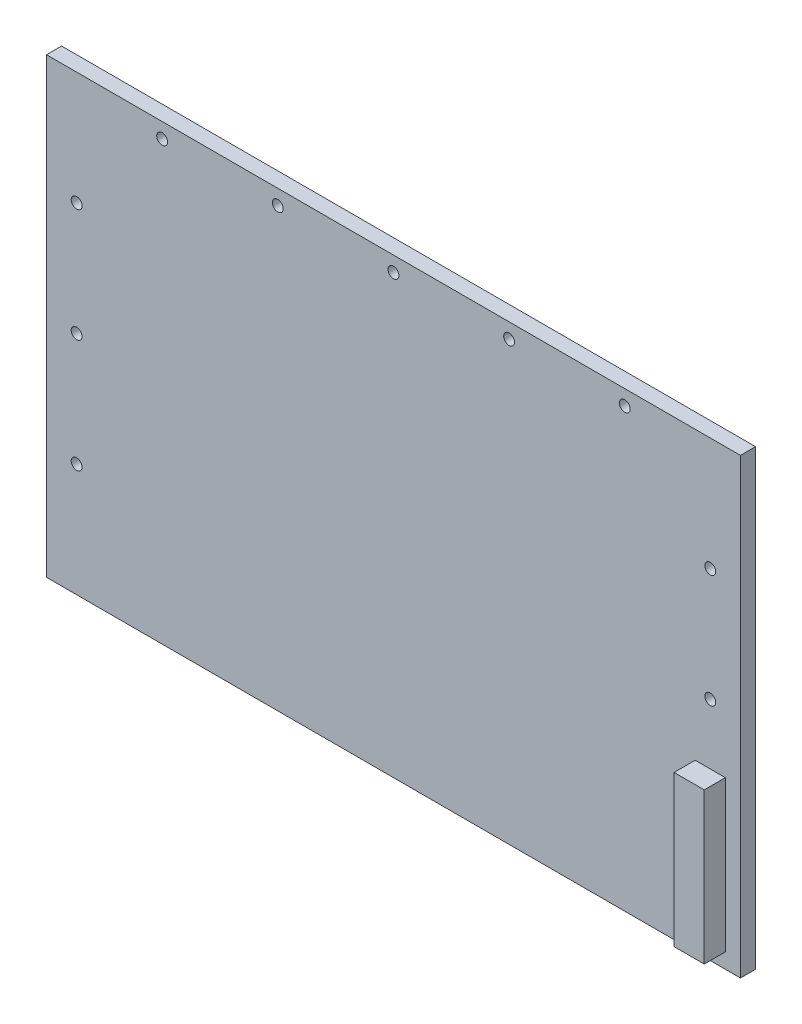
SolidWorks part; units mm, degrees
ref_plane "Płaszczyzna przednia" through (0, 0, 0) normal (0, 0, 1) x (1, 0, 0)
ref_plane "Płaszczyzna górna" through (0, 0, 0) normal (0, 1, 0) x (1, 0, 0)
ref_plane "Płaszczyzna prawa" through (0, 0, 0) normal (1, 0, 0) x (0, 0, -1)
sketch "Szkic1" plane through (0, 0, 0) normal (0, 0, 1) x (1, 0, 0)
  line L1 (-115, -75) -> (115, -75)
  line L2 (-115, -75) -> (-115, 75)
  line L3 (-115, 75) -> (115, 75)
  line L4 (115, -75) -> (115, 75)
  line L5 (0, 75) -> (0, -75) construction
  line L6 (-115, 0) -> (115, 0) construction
  point P0 (0, 0)
  dimension "D1" = 230
  dimension "D2" = 150
extrude "Dodanie-wyciągnięcie1" add sketch "Szkic1" along normal blind 5
sketch "Szkic3" plane through (0, 0, 0) normal (0, 0, -1) x (-1, 0, 0)
  line L0 (0, 75) -> (0, -75) construction
  line L1 (-115, 75) -> (115, 75) construction
  line L2 (115, -75) -> (-115, -75) construction
  point P0 (105, 37.5)
  point P1 (105, 0)
  point P3 (105, -37.5)
  point P16 (-105, 0)
  point P17 (-105, 37.5)
hole_wizard "Pogłębienie walcowe pod M3 Śrubę z łbem stożkowym ściętym1" positions "Szkic3" profile "Szkic4" counterbore size "M3" standard "DIN"
sketch "Szkic4" plane through (-105, 37.5, 0) normal (1, 0, 0) x (0, 1, 0)
  line L0 (0, 0) -> (0, 7.7815)
  line L1 (0, 7.7815) -> (1.8, 6.7)
  line L2 (1.8, 6.7) -> (1.8, 2.4)
  line L3 (1.8, 2.4) -> (3.5, 2.4)
  line L4 (3.5, 2.4) -> (3.5, 0)
  line L5 (3.5, 0) -> (0, 0)
  line L10 (0, 7.7815) -> (-1.8, 6.7) construction
  line L11 (0, -6.35) -> (0, 107.95) construction
  dimension "Średnica otworu" = 3.6
  dimension "Głębokość otworu" = 6.7
  dimension "Średnica pogłębienia walcowego" = 7
  dimension "Głębokość pogłębienia walcowego" = 2.4
  dimension "Kąt wiertła" = 118
sketch "Szkic5" plane through (0, 0, 0) normal (0, 0, -1) x (-1, 0, 0)
  line L0 (-115, 75) -> (115, 75) construction
  line L1 (-115, -75) -> (-115, 75) construction
  point P0 (-76.6667, 70)
  point P5 (-38.3333, 70)
  point P7 (0, 70)
  point P8 (38.3333, 70)
  point P9 (76.6667, 70)
  dimension "D1" = 5
  dimension "D2" = 38.3333
  dimension "D3" = 5
hole_wizard "Pogłębienie walcowe pod M3 Śrubę z łbem stożkowym ściętym2" positions "Szkic5" profile "Szkic6" counterbore size "M3" standard "DIN"
sketch "Szkic6" plane through (76.6667, 70, 0) normal (1, 0, 0) x (0, 1, 0)
  line L0 (0, 0) -> (0, 7.7815)
  line L1 (0, 7.7815) -> (1.8, 6.7)
  line L2 (1.8, 6.7) -> (1.8, 2.4)
  line L3 (1.8, 2.4) -> (3.5, 2.4)
  line L4 (3.5, 2.4) -> (3.5, 0)
  line L5 (3.5, 0) -> (0, 0)
  line L10 (0, 7.7815) -> (-1.8, 6.7) construction
  line L11 (0, -6.35) -> (0, 107.95) construction
  dimension "Średnica otworu" = 3.6
  dimension "Głębokość otworu" = 6.7
  dimension "Średnica pogłębienia walcowego" = 7
  dimension "Głębokość pogłębienia walcowego" = 2.4
  dimension "Kąt wiertła" = 118
sketch "Szkic7" plane through (0, 0, 5) normal (0, 0, 1) x (1, 0, 0)
  line L0 (110, -70) -> (110, -20)
  line L14 (115, -75) -> (115, -20)
  line L15 (115, -20) -> (100, -20)
  line L16 (100, -20) -> (100, -70)
  line L17 (100, -70) -> (110, -70)
  line L18 (110, -70) -> (110, -75)
  line L19 (110, -75) -> (115, -75)
  line L21 (110, -20) -> (100, -20)
  line L22 (100, -20) -> (100, -70)
  line L23 (100, -70) -> (110, -70)
  dimension "D2" = 0
extrude "Dodanie-wyciągnięcie3" add sketch "Szkic7" along normal blind 7
sketch "Szkic8" plane through (0, -70, 0) normal (0, -1, 0) x (1, 0, 0)
  line L0 (100, 12) -> (110, 5) construction
  point P4 (105, 8.5)
hole_wizard "Otwory ustalające Ø4.0mm1" positions "Szkic8" profile "Szkic9" hole size "Ø4.0" standard "DIN"
sketch "Szkic9" plane through (105, -70, 8.5) normal (1, 0, 0) x (0, 0, -1)
  line L0 (0, 0) -> (0, 6.7)
  line L1 (0, 6.7) -> (2, 6.7)
  line L2 (2, 6.7) -> (2, 0)
  line L5 (2, 0) -> (0, 0)
  line L10 (0, 6.7) -> (-2, 6.7) construction
  line L11 (0, -6.35) -> (0, 107.95) construction
  dimension "Średnica otworu" = 4
  dimension "Głębokość otworu" = 6.7
  dimension "Kąt wiertła" = 180
